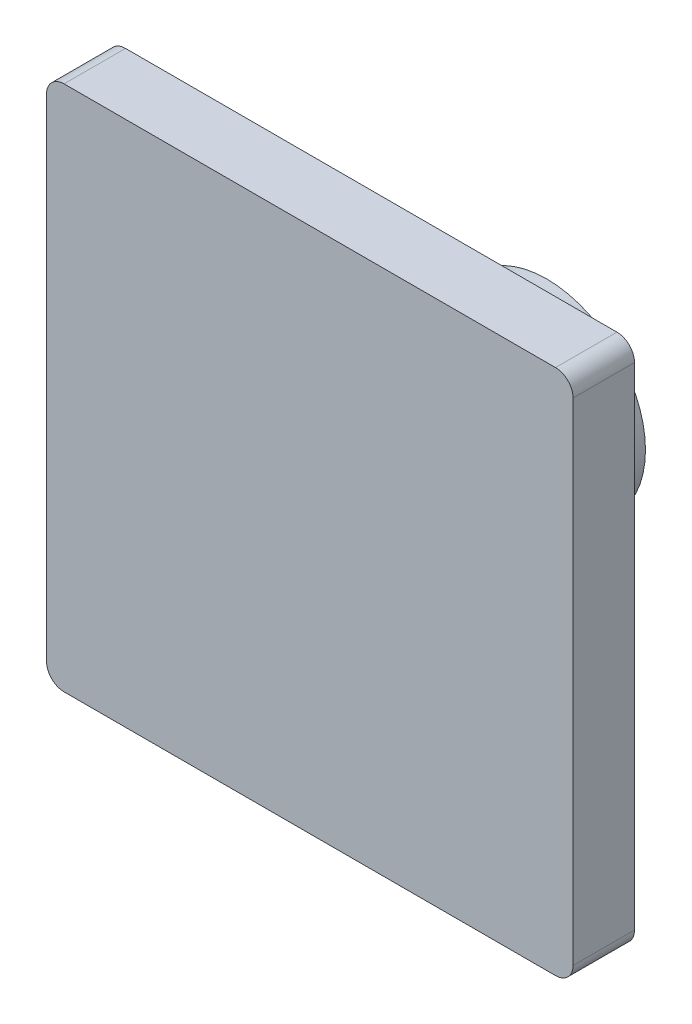
SolidWorks part; units mm, degrees
material "PW80:Mi:0:30:C1:0:1:2:Re:16:"
ref_plane "Plan1" through (0, 0, 0) normal (0, 0, 1) x (1, 0, 0)
ref_plane "Plan2" through (0, 0, 0) normal (0, 1, 0) x (1, 0, 0)
ref_plane "Plan3" through (0, 0, 0) normal (1, 0, 0) x (0, 0, -1)
sketch "Esquisse1" plane through (0, 0, 0) normal (0, 0, 1) x (1, 0, 0)
  line L1 (-30, 30) -> (30, 30)
  line L2 (-30, 30) -> (-30, -30)
  line L3 (-30, -30) -> (30, -30)
  line L4 (30, 30) -> (30, -30)
extrude "Base-Extrusion" add sketch "Esquisse1" along normal blind 7
fillet "Congé2" radius 2
sketch "Esquisse14" plane through (0, 0, 0) normal (0, 0, -1) x (-1, 0, 0)
  circle A0 centre (0, 0) radius 11.25
extrude "Boss.-Extru.12" add sketch "Esquisse14" along normal blind 20
